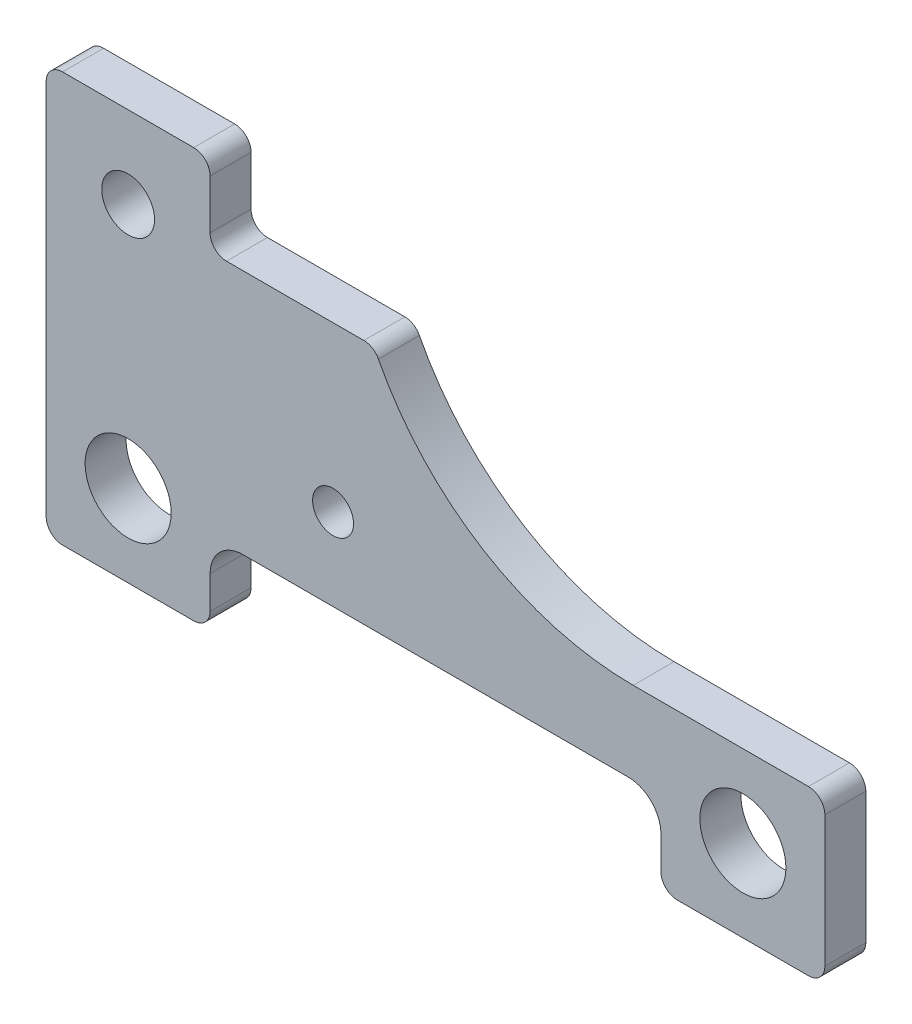
SolidWorks part; units mm, degrees
ref_plane "Front Plane" through (0, 0, 0) normal (0, 0, 1) x (1, 0, 0)
ref_plane "Top Plane" through (0, 0, 0) normal (0, 1, 0) x (1, 0, 0)
ref_plane "Right Plane" through (0, 0, 0) normal (1, 0, 0) x (0, 0, -1)
sketch "Sketch1" plane through (0, 0, 0) normal (0, 0, 1) x (1, 0, 0)
  line L1 (-47.5, 0) -> (-47.5, 50)
  line L2 (-47.5, 50) -> (-27.5, 50)
  line L3 (-27.5, 50) -> (-27.5, 40)
  line L4 (-27.5, 40) -> (-7.5, 40)
  line L6 (47.5, -0.002) -> (47.5, 19.998)
  line L7 (47.5, 19.998) -> (24.1237, 19.998)
  line L8 (-47.5, 0) -> (-27.5, 0)
  line L9 (-27.5, 0) -> (-27.5, 10)
  line L10 (-27.5, 10) -> (27.5, 10)
  line L11 (27.5, 10) -> (27.5, -0.002)
  line L12 (27.5, -0.002) -> (47.5, -0.002)
  arc A0 (-7.5, 40) -> (24.1237, 19.998) centre (24.1237, 54.998) ccw
  circle A1 centre (-37.5, 10) radius 5.25
  circle A2 centre (-37.5, 40) radius 3.225
  circle A3 centre (-12.5, 20) radius 2.5
  circle A4 centre (37.5, 9.998) radius 5.25
  dimension "D8" = 55
  dimension "D9" = 30
  dimension "D10" = 6.45
  dimension "D11" = 10.5
  dimension "D12" = 10.5
  dimension "D1" = 20
  dimension "D2" = 50
  dimension "D3" = 10
  dimension "D4" = 20
  dimension "D5" = 20
  dimension "D6" = 10
  dimension "D7" = 20
extrude "Boss-Extrude1" add sketch "Sketch1" along normal mid plane 5
fillet "Fillet1" radius 4 2 edges at (27.5, 10, 0) (-27.5, 10, 0)
fillet "Fillet3" radius 2 9 edges at (-7.5, 40, 0) (27.5, -0.002, 0) (47.5, -0.002, 0) (47.5, 19.998, 0) (-27.5, 40, 0) (-27.5, 50, 0) (-47.5, 50, 0) (-27.5, 0, 0) (-47.5, 0, 0)
